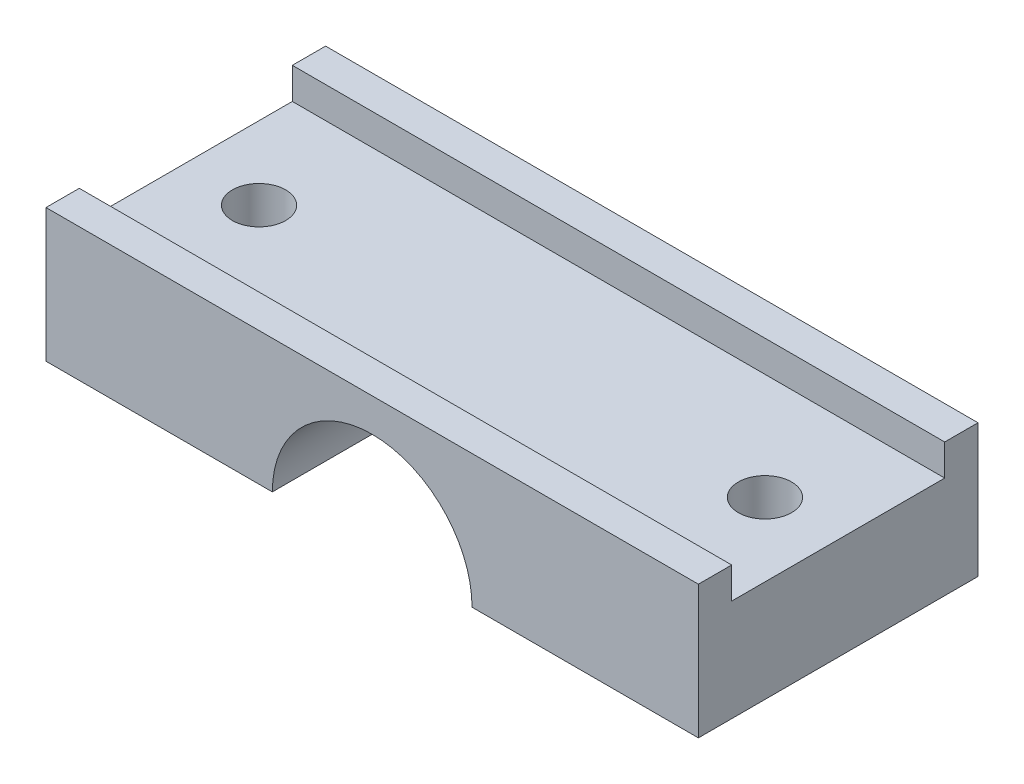
SolidWorks part; units mm, degrees
ref_plane "Front Plane" through (0, 0, 0) normal (0, 0, 1) x (1, 0, 0)
ref_plane "Top Plane" through (0, 0, 0) normal (0, 1, 0) x (1, 0, 0)
ref_plane "Right Plane" through (0, 0, 0) normal (1, 0, 0) x (0, 0, -1)
sketch "Sketch2" plane through (0, 0, 0) normal (0, 0, 1) x (1, 0, 0)
  line L1 (0, 0) -> (98, 0)
  line L2 (0, 0) -> (0, 20)
  line L3 (0, 20) -> (98, 20)
  line L4 (98, 0) -> (98, 20)
  line L5 (49, 20) -> (49, 0) construction
  line L6 (0, 10) -> (98, 10) construction
  point P400 (49, 10)
  dimension "D1" = 20
  dimension "D2" = 98
extrude "Boss-Extrude1" add sketch "Sketch2" along normal blind 42
sketch "Sketch4" plane through (98, 0, 0) normal (1, 0, 0) x (0, 0, -1)
  line L0 (-21, 20) -> (-21, 0) construction
  line L1 (-42, 10) -> (0, 10) construction
  line L2 (-37, 20) -> (-37, 0) construction
  line L3 (-5, 20) -> (-5, 0) construction
  line L4 (0, 0) -> (0, 20)
  line L5 (0, 20) -> (-42, 20)
  line L6 (-42, 20) -> (-42, 0)
  line L7 (-42, 0) -> (0, 0)
  line L8 (0, 0) -> (0, 20)
  line L9 (0, 20) -> (-42, 20)
  line L10 (-42, 20) -> (-42, 0)
  line L11 (-42, 0) -> (0, 0)
  line L12 (-42, 15.3) -> (0, 15.3)
  line L14 (-37, 20) -> (-5, 20)
  line L15 (-37, 20) -> (-37, 15.3)
  line L16 (-37, 15.3) -> (-5, 15.3)
  line L17 (-5, 20) -> (-5, 15.3)
  dimension "D4" = 15.3
  dimension "D1" = 0
  dimension "D2" = 16
  dimension "D3" = 16
extrude "Cut-Extrude1" cut sketch "Sketch4" against normal through all contours L17 L9 L15 L12
sketch "Sketch5" plane through (0, 0, 0) normal (0, 0, -1) x (-1, 0, 0)
  line L3 (-98, 0) -> (-98, 20) construction
  line L4 (0, 0) -> (-98, 0) construction
  circle A1 centre (-49, 39) radius 17.5
  dimension "D1" = 49
  dimension "D2" = 35
  dimension "D3" = 39
sketch "Sketch6" plane through (0, 15.3, 0) normal (0, 1, 0) x (1, 0, 0)
  line L3 (0, 0) -> (98, 0)
  line L4 (0, 0) -> (0, -42)
  line L5 (0, -42) -> (98, -42)
  line L6 (98, 0) -> (98, -42)
  line L7 (49, -42) -> (49, 0) construction
  line L8 (0, -21) -> (98, -21) construction
  circle A0 centre (11, -21) radius 4
  circle A1 centre (87, -21) radius 4
  point P312 (49, -21)
  dimension "D1" = 8
  dimension "D2" = 11
extrude "Cut-Extrude3" cut sketch "Sketch6" against normal through all contours A1 | A0
sketch "Sketch7" plane through (0, 0, 42) normal (0, 0, 1) x (1, 0, 0)
  line L0 (0, 0) -> (98, 0) construction
  circle A0 centre (49, 0) radius 15
  point P2 (49, 0)
  dimension "D1" = 30
extrude "Cut-Extrude4" cut sketch "Sketch7" against normal through all
